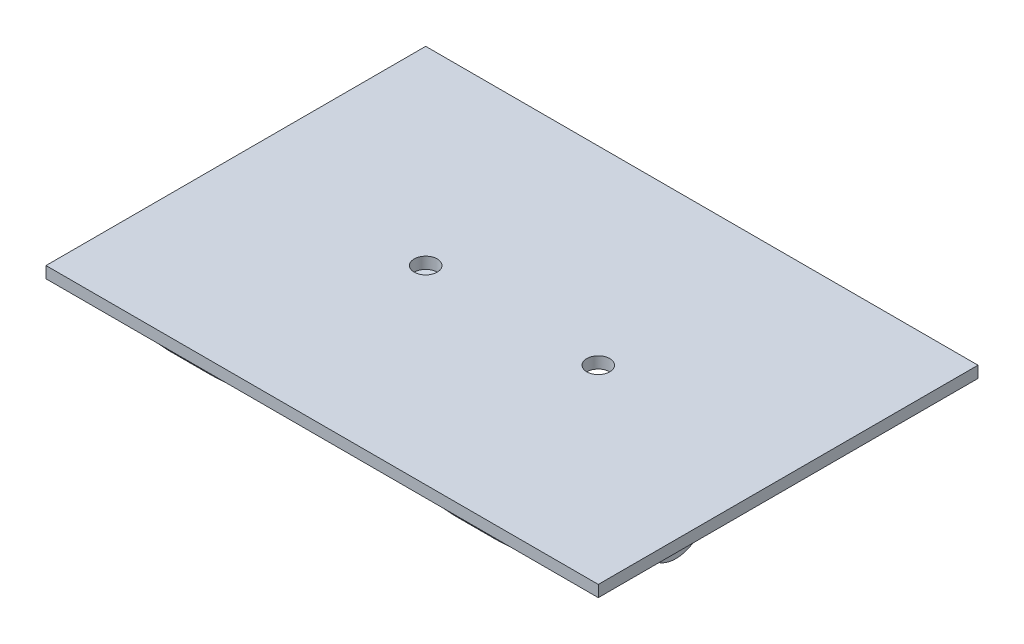
SolidWorks part; units mm, degrees
ref_plane "Front Plane" through (0, 0, 0) normal (0, 0, 1) x (1, 0, 0)
ref_plane "Top Plane" through (0, 0, 0) normal (0, 1, 0) x (1, 0, 0)
ref_plane "Right Plane" through (0, 0, 0) normal (1, 0, 0) x (0, 0, -1)
sketch "Sketch1" plane through (0, 0, 0) normal (0, 1, 0) x (1, 0, 0)
  line L0 (96, 33) -> (63, 33) construction
  line L1 (0, 0) -> (96, 0)
  line L2 (0, 0) -> (0, 66)
  line L3 (0, 66) -> (96, 66)
  line L4 (96, 0) -> (96, 66)
  line L5 (65, 33) -> (63, 31) construction
  line L6 (63, 31) -> (61, 33) construction
  line L7 (35, 33) -> (33, 31) construction
  line L8 (33, 31) -> (31, 33) construction
  line L9 (0, 33) -> (33, 33) construction
  circle A0 centre (33, 33) radius 2
  circle A1 centre (63, 33) radius 2
  dimension "D1" = 26
  dimension "D2" = 96
  dimension "D3" = 66
  dimension "D4" = 34
extrude "Boss-Extrude1" add sketch "Sketch1" along normal blind 2
ref_plane "Plane1" through (48, 0, 0) normal (-1, 0, 0) x (0, 0, 1)
ref_plane "Plane2" through (0, 0, -33) normal (0, 0, -1) x (-1, 0, 0)
ref_plane "Plane3" through (27, 0, 0) normal (-1, 0, 0) x (0, 0, 1)
sketch "Sketch8" plane through (27, 0, 0) normal (-1, 0, 0) x (0, 0, 1)
  line L0 (-33, 0) -> (-33, -15) construction
  line L1 (0, 0) -> (-66, 0) construction
  line L2 (-8.5174, 0) -> (0, 0)
  line L3 (-66, 0) -> (-57.4826, 0)
  arc A2 (-66, 0) -> (0, 0) centre (-33, 28.8) ccw construction
  arc A3 (-57.4826, 0) -> (-8.5174, 0) centre (-33, 28.8) ccw construction
  circle A5 centre (-33, -15) radius 2.375
  arc A8 (-27.6351, -14.6702) -> (0, 0) centre (-33, 28.8) ccw
  arc A9 (-66, 0) -> (-38.3649, -14.6702) centre (-33, 28.8) ccw
  arc A11 (-38.3649, -14.6702) -> (-27.6351, -14.6702) centre (-33, -15) ccw
  arc A12 (-8.5174, 0) -> (-57.4826, 0) centre (-33, 28.8) cw
  dimension "D2" = 6
  dimension "D3" = 3
  dimension "D4" = 4.75
  dimension "D1" = 15
extrude "Boss-Extrude3" add sketch "Sketch8" along normal blind 7.5
mirror "Mirror1" about plane through (48, 0, 0) normal (-1, 0, 0) of "Boss-Extrude3"
sketch "Sketch9" plane through (76.5, 0, 0) normal (1, 0, 0) x (0, 0, -1)
  circle A0 centre (33, -15) radius 2.55
  dimension "D1" = 5.1
extrude "Cut-Extrude1" cut sketch "Sketch9" against normal up to surface (7.5 mm away) up to face at (69, -15, -30.625)
